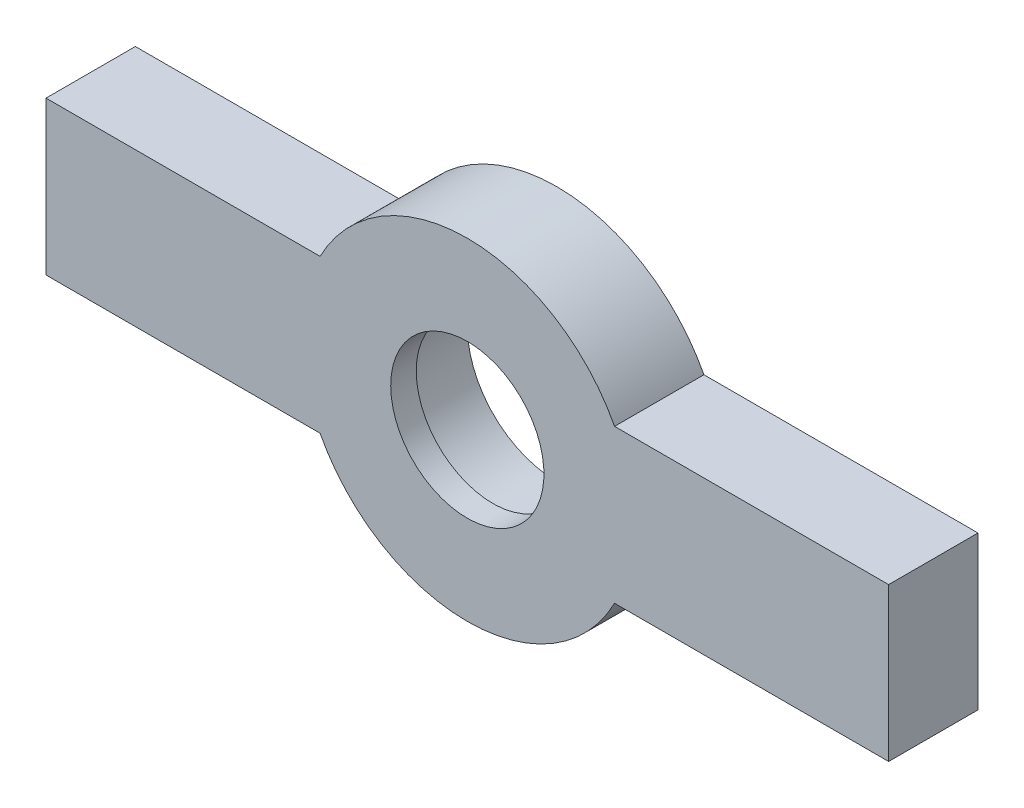
SolidWorks part; units mm, degrees
ref_plane "Plano frontal" through (0, 0, 0) normal (0, 0, 1) x (1, 0, 0)
ref_plane "Plano superior" through (0, 0, 0) normal (0, 1, 0) x (1, 0, 0)
ref_plane "Plano direito" through (0, 0, 0) normal (1, 0, 0) x (0, 0, -1)
sketch "Esboço1" plane through (0, 0, 0) normal (0, 0, 1) x (1, 0, 0)
  line L0 (-257.6628, -210) -> (-365, -210)
  line L1 (-35, -210) -> (-142.3372, -210)
  line L2 (-35, -210) -> (-35, -270)
  line L3 (-35, -270) -> (-142.3372, -270)
  line L4 (-365, -210) -> (-365, -270)
  line L5 (-257.6628, -270) -> (-365, -270)
  arc A0 (-142.3372, -210) -> (-257.6628, -210) centre (-200, -240) ccw
  arc A1 (-257.6628, -270) -> (-142.3372, -270) centre (-200, -240) ccw
extrude "Ressalto-extrusão1" add sketch "Esboço1" against normal blind 35
sketch "Esboço2" plane through (0, 0, -35) normal (0, 0, -1) x (-1, 0, 0)
  circle A0 centre (200, -240) radius 35
  arc A1 (142.3372, -270) -> (257.6628, -270) centre (200, -240) ccw construction
  dimension "D1" = 70
extrude "Corte-extrusão1" cut sketch "Esboço2" against normal blind 25
sketch "Esboço3" plane through (0, 0, -10) normal (0, 0, -1) x (-1, 0, 0)
  circle A0 centre (200, -240) radius 30
  circle A1 centre (200, -240) radius 35 construction
  dimension "D1" = 60
extrude "Corte-extrusão2" cut sketch "Esboço3" against normal through all
